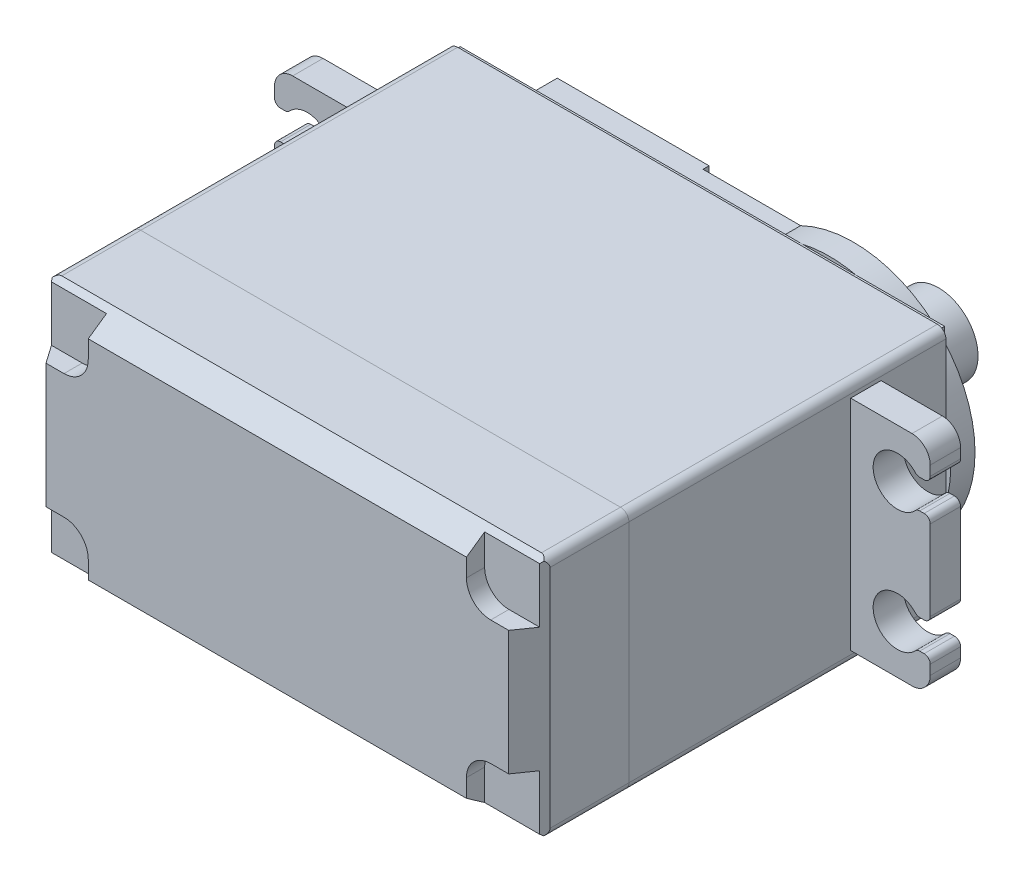
SolidWorks part; units mm, degrees
ref_plane "Front Plane" through (0, 0, 0) normal (0, 0, 1) x (1, 0, 0)
ref_plane "Top Plane" through (0, 0, 0) normal (0, 1, 0) x (1, 0, 0)
ref_plane "Right Plane" through (0, 0, 0) normal (1, 0, 0) x (0, 0, -1)
sketch "Sketch1" plane through (0, 0, 0) normal (0, 0, 1) x (1, 0, 0)
  line L1 (-20.45, -10) -> (20.45, -10)
  line L2 (-20.45, -10) -> (-20.45, 10)
  line L3 (-20.45, 10) -> (20.45, 10)
  line L4 (20.45, -10) -> (20.45, 10)
  line L5 (-20.45, -10) -> (20.45, 10) construction
  line L6 (-20.45, 10) -> (20.45, -10) construction
  point P0 (0, 0)
  dimension "D1" = 20
  dimension "D2" = 40.9
extrude "Boss-Extrude3" add sketch "Sketch1" along normal blind 19.3
sketch "Sketch4" plane through (0, 0, 0) normal (0, 0, -1) x (-1, 0, 0)
  line L4 (-20.45, 10) -> (-20.45, -10)
  line L5 (-20.45, -10) -> (20.45, -10)
  line L6 (20.45, -10) -> (20.45, 10)
  line L7 (20.45, 10) -> (-20.45, 10)
  line L8 (-20.45, 10) -> (-20.45, -10)
  line L9 (-20.45, -10) -> (20.45, -10)
  line L10 (20.45, -10) -> (20.45, 10)
  line L11 (20.45, 10) -> (-20.45, 10)
  dimension "D1" = 0
extrude "Boss-Extrude4" add sketch "Sketch4" along normal blind 6.8 separate body
sketch "Sketch5" plane through (0, 0, -6.8) normal (0, 0, -1) x (-1, 0, 0)
  line L4 (20.45, 10) -> (-20.45, 10)
  line L5 (-20.45, 10) -> (-20.45, -10)
  line L6 (-20.45, -10) -> (20.45, -10)
  line L7 (20.45, -10) -> (20.45, 10)
  line L8 (20.45, 10) -> (-20.45, 10)
  line L9 (-20.45, 10) -> (-20.45, -10)
  line L10 (-20.45, -10) -> (20.45, -10)
  line L11 (20.45, -10) -> (20.45, 10)
  dimension "D1" = 0
sketch "Sketch6" plane through (0, 0, 19.3) normal (0, 0, 1) x (1, 0, 0)
  line L4 (20.45, -10) -> (20.45, 10)
  line L5 (20.45, 10) -> (-20.45, 10)
  line L6 (-20.45, 10) -> (-20.45, -10)
  line L7 (-20.45, -10) -> (20.45, -10)
  line L8 (20.45, -10) -> (20.45, 10)
  line L9 (20.45, 10) -> (-20.45, 10)
  line L10 (-20.45, 10) -> (-20.45, -10)
  line L11 (-20.45, -10) -> (20.45, -10)
  dimension "D1" = 0
extrude "Boss-Extrude6" add sketch "Sketch6" along normal blind 8.5 separate body
chamfer "Chamfer1" distance 2 angle 35 4 edges at (-20.45, 0, 27.8) (0, 10, 27.8) (20.45, 0, 27.8) (0, -10, 27.8)
sketch "Sketch7" plane through (0, 0, 27.8) normal (0, 0, 1) x (1, 0, 0)
  line L0 (0, 0) -> (0, 10) construction
  line L1 (-20.45, 10) -> (-15.57, 10)
  line L2 (-20.45, 10) -> (-20.45, 5.12)
  line L3 (-20.45, 5.12) -> (-17.57, 5.12)
  line L4 (-15.57, 10) -> (-15.57, 7.12)
  line L5 (-20.45, 10) -> (20.45, 10) construction
  line L6 (0, 0) -> (20.45, 0) construction
  line L7 (20.45, 10) -> (20.45, -10) construction
  line L8 (20.45, 5.12) -> (17.57, 5.12)
  line L9 (15.57, 10) -> (15.57, 7.12)
  line L10 (20.45, 10) -> (15.57, 10)
  line L11 (20.45, 10) -> (20.45, 5.12)
  line L12 (20.45, -10) -> (20.45, -5.12)
  line L13 (20.45, -10) -> (15.57, -10)
  line L14 (15.57, -10) -> (15.57, -7.12)
  line L15 (20.45, -5.12) -> (17.57, -5.12)
  line L16 (-15.57, -10) -> (-15.57, -7.12)
  line L17 (-20.45, -5.12) -> (-17.57, -5.12)
  line L18 (-20.45, -10) -> (-20.45, -5.12)
  line L19 (-20.45, -10) -> (-15.57, -10)
  arc A0 (-17.57, 5.12) -> (-15.57, 7.12) centre (-17.57, 7.12) ccw
  arc A1 (17.57, 5.12) -> (15.57, 7.12) centre (17.57, 7.12) cw
  arc A2 (17.57, -5.12) -> (15.57, -7.12) centre (17.57, -7.12) ccw
  arc A3 (-17.57, -5.12) -> (-15.57, -7.12) centre (-17.57, -7.12) cw
  dimension "D3" = 2
  dimension "D1" = 4.88
  dimension "D2" = 4.88
extrude "Cut-Extrude1" cut sketch "Sketch7" against normal blind 1.5
sketch "Sketch8" plane through (0, 0, -6.8) normal (0, 0, -1) x (-1, 0, 0)
  line L0 (20.45, 10) -> (-20.45, 10) construction
  line L1 (19.95, -9.75) -> (-19.95, -9.75)
  line L2 (19.95, -9.75) -> (19.95, 9.75)
  line L3 (19.95, 9.75) -> (-19.95, 9.75)
  line L4 (-19.95, -9.75) -> (-19.95, 9.75)
  line L5 (19.95, -9.75) -> (-19.95, 9.75) construction
  line L6 (19.95, 9.75) -> (-19.95, -9.75) construction
  line L7 (20.45, -10) -> (20.45, 10) construction
  point P0 (0, 0)
  dimension "D1" = 0.25
  dimension "D2" = 0.5
extrude "Boss-Extrude7" add sketch "Sketch8" along normal blind 0.4
sketch "Sketch9" plane through (0, 0, -7.2) normal (0, 0, -1) x (-1, 0, 0)
  line L0 (-20.45, 0) -> (20.45, 0) construction
  line L1 (-20.45, 10) -> (-20.45, -10) construction
  line L2 (20.45, -10) -> (20.45, 10) construction
  line L3 (20.45, 10) -> (-20.45, 10) construction
  line L4 (-6.09, 10) -> (-6.09, -10) construction
  line L5 (-20.45, -10) -> (20.45, -10) construction
  line L6 (-6.09, 8.9995) -> (14.45, 8.9995)
  line L7 (14.45, 8.9995) -> (14.45, 3)
  line L8 (14.45, -8.9995) -> (14.45, -3)
  line L9 (-6.09, -8.9995) -> (14.45, -8.9995)
  arc A0 (-6.09, 8.9995) -> (-6.09, -8.9995) centre (-10.45, 0) ccw
  arc A1 (14.45, -3) -> (14.45, 3) centre (14.45, 0) ccw
  point P21 (17.45, 0)
  dimension "D1" = 14.36
  dimension "D2" = 6
  dimension "D3" = 3
extrude "Boss-Extrude8" add sketch "Sketch9" along normal blind 2
sketch "Sketch10" plane through (0, 0, -9.2) normal (0, 0, -1) x (-1, 0, 0)
  circle A0 centre (-10.45, 0) radius 6.5
  dimension "D1" = 13
extrude "Boss-Extrude9" add sketch "Sketch10" along normal blind 1.5
sketch "Sketch11" plane through (0, 0, -10.7) normal (0, 0, -1) x (-1, 0, 0)
  circle A0 centre (-10.45, 0) radius 5.5
  dimension "D1" = 11
extrude "Boss-Extrude10" add sketch "Sketch11" along normal blind 0.5
sketch "Sketch12" plane through (0, 0, -11.2) normal (0, 0, -1) x (-1, 0, 0)
  circle A0 centre (-10.45, 0) radius 3.25
  dimension "D1" = 6.5
extrude "Boss-Extrude11" add sketch "Sketch12" along normal blind 5
sketch "Sketch13" plane through (0, 0, -9.2) normal (0, 0, -1) x (-1, 0, 0)
  line L0 (-6.09, -8.9995) -> (14.45, -8.9995) construction
  line L1 (14.45, 8.9995) -> (1.95, 8.9995)
  line L2 (14.45, 8.9995) -> (14.45, -8.9995)
  line L3 (14.45, -8.9995) -> (1.95, -8.9995)
  line L4 (1.95, 8.9995) -> (1.95, 1.75)
  line L5 (13.45, 7.9995) -> (2.95, 7.9995)
  line L6 (2.95, 7.9995) -> (2.95, -7.9995)
  line L7 (13.45, -7.9995) -> (2.95, -7.9995)
  line L8 (13.45, 7.9995) -> (13.45, -7.9995)
  line L9 (1.95, -1.75) -> (1.95, -8.9995)
  line L11 (1.95, 8.9995) -> (1.95, -8.9995) construction
  arc A0 (1.95, 1.75) -> (1.95, -1.75) centre (1.95, 0) ccw
  dimension "D3" = 3.5
  dimension "D1" = 12.5
  dimension "D2" = 1
extrude "Boss-Extrude12" add sketch "Sketch13" along normal blind 0.5
fillet "Fillet1" radius 0.7 4 edges at (-20.45, -10, 9.65) (-20.45, 10, 9.65) (20.45, 10, 9.65) (20.45, -10, 9.65)
fillet "Fillet6" radius 0.7 4 edges at (-20.45, 10, -3.4) (-20.45, -10, -3.4) (20.45, 10, -3.4) (20.45, -10, -3.4)
fillet "Fillet7" radius 0.7 4 edges at (-20.45, -10, 22.55) (20.45, -10, 22.55) (-20.45, 10, 22.55) (20.45, 10, 22.55)
sketch "Sketch16" plane through (0, 0, -7.2) normal (0, 0, -1) x (-1, 0, 0)
  line L0 (20.45, 9) -> (25.5, 9)
  line L1 (20.45, -10) -> (20.45, 10) construction
  line L2 (0.2, 0) -> (27, 0) construction
  line L3 (27, 7.5) -> (27, 6.7)
  line L4 (20.45, 10) -> (-20.45, 10) construction
  line L5 (0, 10) -> (0, -8.9995) construction
  line L6 (-6.09, -8.9995) -> (1.95, -8.9995) construction
  line L7 (25.9, 9) -> (25.9, -9) construction
  line L8 (26.133, 6.2) -> (26.5, 6.2)
  line L9 (26.133, 3.8) -> (26.5, 3.8)
  line L10 (27, 3.3) -> (27, -3.3)
  line L11 (26.133, -3.8) -> (26.5, -3.8)
  line L12 (26.133, -6.2) -> (26.5, -6.2)
  line L13 (27, -7.5) -> (27, -6.7)
  line L14 (20.45, -9) -> (25.5, -9)
  line L15 (20.45, 9) -> (20.45, -9)
  arc A0 (1.95, 1.75) -> (1.95, -1.75) centre (1.95, 0) ccw construction
  arc A1 (25.7664, 6.36) -> (25.7664, 3.64) centre (24.3, 5) ccw
  arc A2 (25.7664, 3.64) -> (26.133, 3.8) centre (26.133, 3.3) cw
  arc A3 (25.7664, 6.36) -> (26.133, 6.2) centre (26.133, 6.7) ccw
  arc A4 (26.5, 3.8) -> (27, 3.3) centre (26.5, 3.3) cw
  arc A5 (26.5, 6.2) -> (27, 6.7) centre (26.5, 6.7) ccw
  arc A6 (25.5, 9) -> (27, 7.5) centre (25.5, 7.5) cw
  arc A7 (25.5, -9) -> (27, -7.5) centre (25.5, -7.5) ccw
  arc A8 (26.5, -6.2) -> (27, -6.7) centre (26.5, -6.7) cw
  arc A9 (26.5, -3.8) -> (27, -3.3) centre (26.5, -3.3) ccw
  arc A10 (25.7664, -6.36) -> (26.133, -6.2) centre (26.133, -6.7) cw
  arc A11 (25.7664, -3.64) -> (26.133, -3.8) centre (26.133, -3.3) ccw
  arc A12 (25.7664, -6.36) -> (25.7664, -3.64) centre (24.3, -5) cw
  point P26 (25.9, 3.8)
  point P29 (25.9, 6.2)
  point P32 (27, 3.8)
  point P38 (25.9, 0)
  point P55 (27, -3.8)
  point P56 (25.9, -6.2)
  point P57 (25.9, -3.8)
  dimension "D3" = 4
  dimension "D7" = 0.5
  dimension "D8" = 1.5
  dimension "D1" = 6.55
  dimension "D2" = 1
  dimension "D4" = 5
  dimension "D5" = 24.3
  dimension "D6" = 1.1
extrude "Boss-Extrude13" add sketch "Sketch16" against normal blind 2.5 from offset 5.74 offset against normal yes
mirror "Mirror1" about plane through (0, 0, 0) normal (1, 0, 0) of "Boss-Extrude13"
